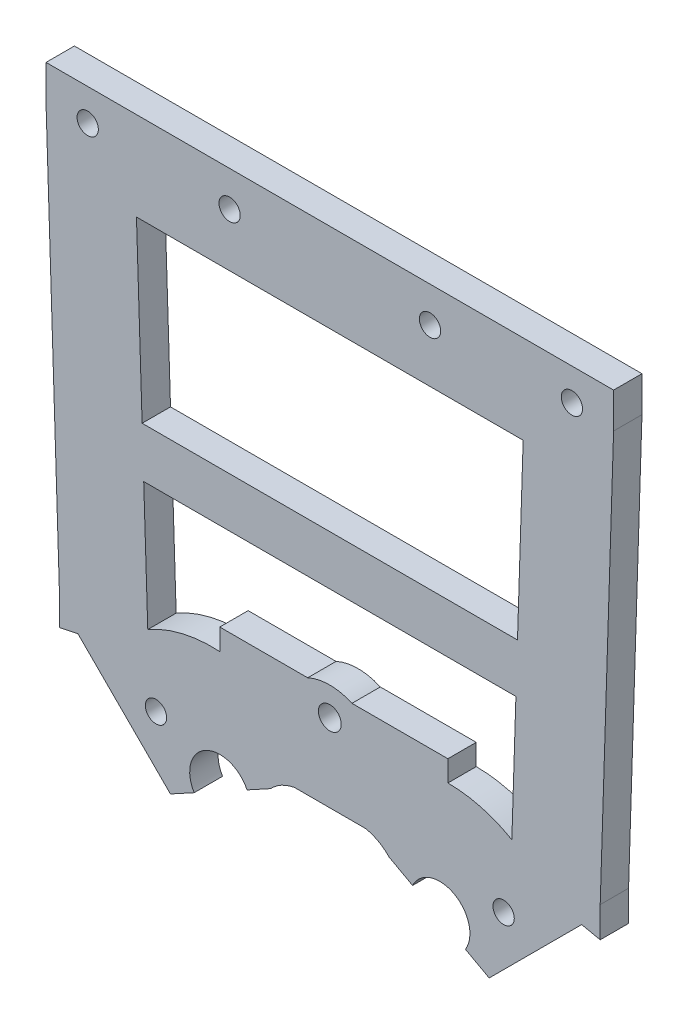
SolidWorks part; units mm, degrees
ref_plane "Front Plane" through (0, 0, 0) normal (0, 0, 1) x (1, 0, 0)
ref_plane "Top Plane" through (0, 0, 0) normal (0, 1, 0) x (1, 0, 0)
ref_plane "Right Plane" through (0, 0, 0) normal (1, 0, 0) x (0, 0, -1)
sketch "Sketch1" plane through (0, 0, 0) normal (0, 0, 1) x (1, 0, 0)
  line L4 (-38.1107, 5.9045) -> (-38.1107, 1.6103)
  line L6 (38.1107, 5.9045) -> (38.1107, 1.6103)
  line L10 (0, 9.6619) -> (0, 69.6619) construction
  line L20 (40, 64.6619) -> (40, 69.6619)
  line L24 (40, 69.6619) -> (-40, 69.6619)
  line L26 (-40, 64.6619) -> (-40, 69.6619)
  line L27 (-40, 64.6619) -> (-38.1107, 5.9045)
  line L28 (38.1107, 5.9045) -> (40, 64.6619)
  line L29 (-27.2524, 57.1619) -> (-26.4556, 32.3819)
  line L30 (-25.6588, 7.602) -> (-25.6588, 7.602)
  line L31 (-25.6588, 7.602) -> (-25.6588, 7.602)
  line L32 (-25.6588, 7.602) -> (-25.6588, 7.602)
  line L34 (25.6588, 7.602) -> (25.6588, 7.602)
  line L35 (25.6588, 7.602) -> (25.6588, 7.602)
  line L36 (25.6588, 7.602) -> (25.6588, 7.602)
  line L37 (25.6588, 7.602) -> (26.2305, 25.3819)
  line L38 (27.2524, 57.1619) -> (27.2524, 57.1619)
  line L39 (27.2524, 57.1619) -> (-27.2524, 57.1619)
  line L40 (-27.2524, 57.1619) -> (-27.2524, 57.1619)
  line L41 (-26.4556, 32.3819) -> (26.4556, 32.3819)
  line L42 (-26.2305, 25.3819) -> (26.2305, 25.3819)
  line L43 (26.4556, 32.3819) -> (27.2524, 57.1619)
  line L44 (25.6588, 7.602) -> (27.2524, 57.1619) construction
  line L45 (-26.2305, 25.3819) -> (-25.6588, 7.602)
  line L46 (-27.2524, 57.1619) -> (-25.6588, 7.602) construction
  line L47 (-15.5116, 9.9826) -> (-15.5116, 12.9826)
  line L48 (-15.5116, 12.9826) -> (16.6399, 12.9826)
  line L49 (16.6399, 12.9826) -> (16.6399, 10.0179)
  line L51 (-5.7409, 6.354) -> (5.7409, 6.354) construction
  line L52 (-38.1107, 1.6103) -> (-30.3544, -6.146) construction
  line L53 (30.3544, -6.146) -> (38.1107, 1.6103) construction
  line L54 (-30.3544, -6.146) -> (-21.8544, -6.146) construction
  line L55 (30.3544, -6.146) -> (21.8544, -6.146) construction
  line L56 (-11.4254, -6.146) -> (11.4254, -6.146) construction
  line L65 (-38.1107, 1.6103) -> (-35.5, 2.1619)
  line L66 (38.1107, 1.6103) -> (35.5, 2.1619)
  line L67 (-22.4645, -10.8737) -> (-5, -1.3381)
  line L68 (5, -1.3381) -> (22.4645, -10.8737)
  circle A8 centre (0, 9.6619) radius 1.6103
  circle A21 centre (34.1245, 65.1619) radius 1.5
  circle A23 centre (14.1245, 64.6619) radius 1.5
  circle A25 centre (-14.1245, 64.6619) radius 1.5
  circle A27 centre (-34.1245, 65.1619) radius 1.5
  arc A29 (-15.5116, 9.9826) -> (-25.6588, 7.602) centre (-16.6399, -8.0247) ccw
  arc A30 (25.6588, 7.602) -> (16.6399, 10.0179) centre (16.6399, -8.0247) ccw
  arc A31 (-5.7409, 6.354) -> (-25.6588, 7.602) centre (-16.6399, -8.0247) ccw construction
  arc A32 (25.6588, 7.602) -> (5.7409, 6.354) centre (16.6399, -8.0247) ccw construction
  arc A33 (-11.4254, -6.146) -> (-21.8544, -6.146) centre (-16.6399, -8.0247) ccw construction
  arc A34 (21.8544, -6.146) -> (11.4254, -6.146) centre (16.6399, -8.0247) ccw construction
  point P2 (0, 69.6619)
  line B0 (15, -12.3381) -> (18.9289, -12.3381)
  line B1 (-15, -12.3381) -> (-18.9289, -12.3381)
  line B2 (5, -1.3381) -> (-5, -1.3381)
  line B3 (-35.5, 2.1619) -> (-22.4645, -10.8737)
  line B4 (-35.5, 6.1619) -> (-35.5, 2.1619)
  line B5 (22.4645, -10.8737) -> (35.5, 2.1619)
  line B6 (35.5, 6.1619) -> (35.5, 2.1619)
  line B7 (10.7819, 6.1619) -> (35.5, 6.1619)
  line B8 (-35.5, 6.1619) -> (-10.7819, 6.1619)
  circle B9 centre (-15.5, -6.8131) radius 1.75
  circle B10 centre (15.5, -6.8131) radius 1.75
  arc B11 (10, -7.3381) -> (5, -1.3381) centre (3.9, -7.3381) ccw
  arc B12 (10, -7.3381) -> (15, -12.3381) centre (15, -7.3381) ccw
  arc B13 (18.9289, -12.3381) -> (22.4645, -10.8737) centre (18.9289, -7.3381) ccw
  arc B14 (-22.4645, -10.8737) -> (-18.9289, -12.3381) centre (-18.9289, -7.3381) ccw
  arc B15 (-15, -12.3381) -> (-10, -7.3381) centre (-15, -7.3381) ccw
  arc B16 (-5, -1.3381) -> (-10, -7.3381) centre (-3.9, -7.3381) ccw
  circle B17 centre (0, 9.6619) radius 1.5
  circle B18 centre (-24.5, -1.8381) radius 1.5
  circle B19 centre (24.5, -1.8381) radius 1.5
  arc B20 (7.0317, 8.7706) -> (10.7819, 6.1619) centre (10.7819, 10.1619) ccw
  arc B21 (-10.7819, 6.1619) -> (-7.0317, 8.7706) centre (-10.7819, 10.1619) ccw
  arc B22 (7.0317, 8.7706) -> (-7.0317, 8.7706) centre (0, 6.1619) ccw
  dimension "D3" = 60
  dimension "D4" = 12.5
  dimension "D5" = 7
  dimension "D6" = 3
sketch_block_instance "Block1-1"
sketch_block "Block1"
extrude "Boss-Extrude1" add sketch "Sketch1" along normal blind 4 contours B22 B20 B7 B6 L66 L6 L28 L20 L24 L26 L27 L4 L65 B4 B8 B21 L48 L47 A29 L45 L42 L37 A30 L49 L43 L41 L29 L39 A21 A23 A25 A27 | L48 B22 | B20 B22 L48 B21 B8 B4 B3 L67 B9 B16 B2 B11 L68 B10 B5 B6 B7 A8 B18 B19
sketch "Sketch2" plane through (0, 0, 4) normal (0, 0, 1) x (1, 0, 0)
  line L0 (-22.4645, -10.8737) -> (-16.9146, -7.8434) construction
  line L1 (-13.8684, -6.1803) -> (-8.3525, -3.1686) construction
  line L2 (-19.1164, -9.0456) -> (-16.9146, -7.8434)
  line L3 (-13.8684, -6.1803) -> (-11.6666, -4.9781)
  line L4 (16.9146, -7.8434) -> (22.4645, -10.8737) construction
  line L5 (8.3525, -3.1686) -> (13.8684, -6.1803) construction
  line L6 (16.9146, -7.8434) -> (19.1164, -9.0456)
  line L7 (11.6666, -4.9781) -> (13.8684, -6.1803)
  arc A6 (-13.8684, -6.1803) -> (-16.9146, -7.8434) centre (-15.5, -6.8131) ccw construction
  arc A7 (-11.5376, -5.2762) -> (-18.9354, -9.3153) centre (-15.5, -6.8131) ccw
  arc A8 (-11.6666, -4.9781) -> (-19.1164, -9.0456) centre (-15.5, -6.8131) ccw
  arc A9 (-13.8684, -6.1803) -> (-16.9146, -7.8434) centre (-15.5, -6.8131) ccw
  arc A11 (16.9146, -7.8434) -> (13.8684, -6.1803) centre (15.5, -6.8131) ccw construction
  arc A12 (18.9354, -9.3153) -> (11.5376, -5.2762) centre (15.5, -6.8131) ccw
  arc A13 (19.1164, -9.0456) -> (11.6666, -4.9781) centre (15.5, -6.8131) ccw
  arc A14 (16.9146, -7.8434) -> (13.8684, -6.1803) centre (15.5, -6.8131) ccw
  dimension "D1" = 2.5
  dimension "D2" = 2.5
extrude "Cut-Extrude1" cut sketch "Sketch2" against normal up to surface (4 mm away) up to face at (0.224, 13.992, 0)
